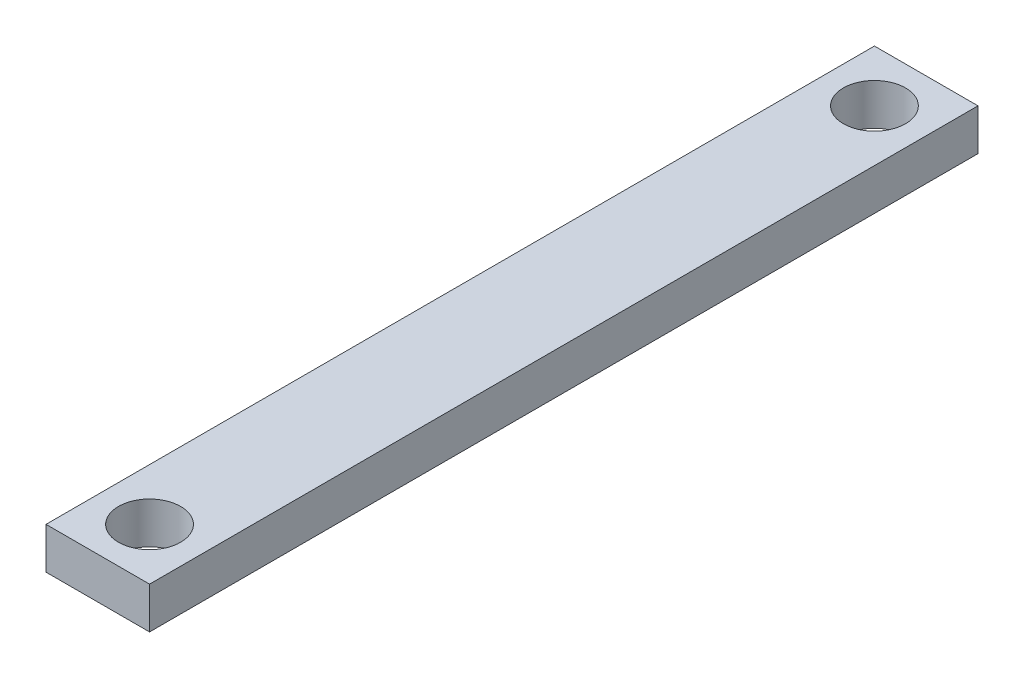
SolidWorks part; units mm, degrees
ref_plane "前视基准面" through (0, 0, 0) normal (0, 0, 1) x (1, 0, 0)
ref_plane "上视基准面" through (0, 0, 0) normal (0, 1, 0) x (1, 0, 0)
ref_plane "右视基准面" through (0, 0, 0) normal (1, 0, 0) x (0, 0, -1)
other "Configuration Table"
sketch "草图1" plane through (0, 0, 0) normal (0, 1, 0) x (1, 0, 0)
  line L1 (0, 0) -> (5, 0)
  line L2 (0, 0) -> (0, -40)
  line L3 (0, -40) -> (5, -40)
  line L4 (5, 0) -> (5, -40)
  circle A6 centre (2.5, -2.5) radius 1.5
  circle A10 centre (2.5, -37.5) radius 1.5
  point P7 (0, 0)
  point P8 (2.5, 0)
  dimension "D29" = 40
  dimension "D3" = 3
  dimension "D1" = 5
  dimension "D4" = 2.5
  dimension "D5" = 2.5
extrude "凸台-拉伸1" add sketch "草图1" along normal blind 2
